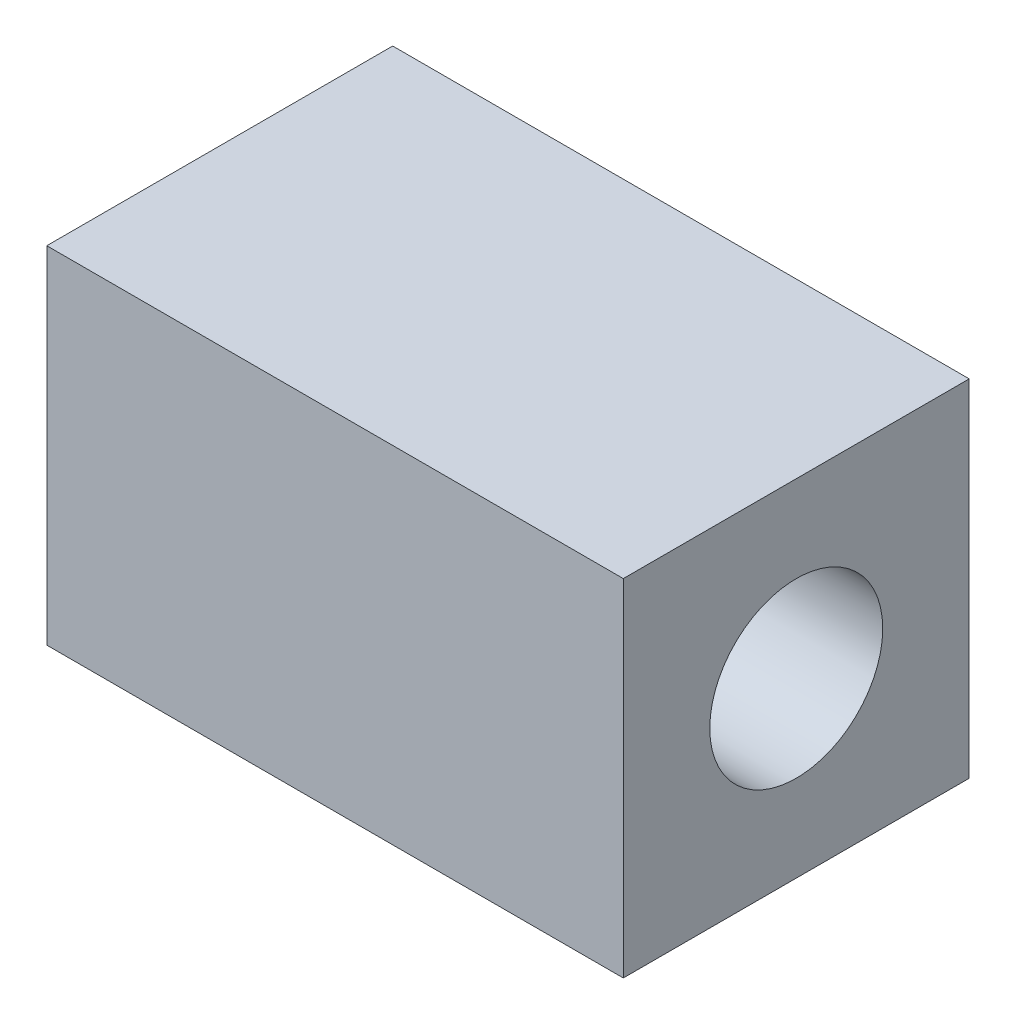
SolidWorks part; units mm, degrees
ref_plane "Alzado" through (0, 0, 0) normal (0, 0, 1) x (1, 0, 0)
ref_plane "Planta" through (0, 0, 0) normal (0, 1, 0) x (1, 0, 0)
ref_plane "Vista lateral" through (0, 0, 0) normal (1, 0, 0) x (0, 0, -1)
sketch "Croquis1" plane through (0, 0, 0) normal (0, 0, 1) x (1, 0, 0)
  line L0 (-134.5288, 0) -> (151.8279, 0) construction
  line L2 (-89.2278, -15) -> (-39.2278, -15)
  line L3 (-89.2278, -15) -> (-89.2278, 15)
  line L4 (-89.2278, 15) -> (-39.2278, 15)
  line L5 (-39.2278, -15) -> (-39.2278, 15)
  line L6 (-89.2278, -15) -> (-39.2278, 15) construction
  line L7 (-89.2278, 15) -> (-39.2278, -15) construction
  point P3 (-64.2278, 0)
  dimension "D1" = 50
  dimension "D2" = 30
extrude "Saliente-Extruir1" add sketch "Croquis1" along normal mid plane 30
sketch "Croquis2" plane through (-89.2278, 0, 0) normal (-1, 0, 0) x (0, 0, 1)
  circle A0 centre (0, 0) radius 7.5
  dimension "D1" = 15
extrude "Cortar-Extruir1" cut sketch "Croquis2" against normal through all
